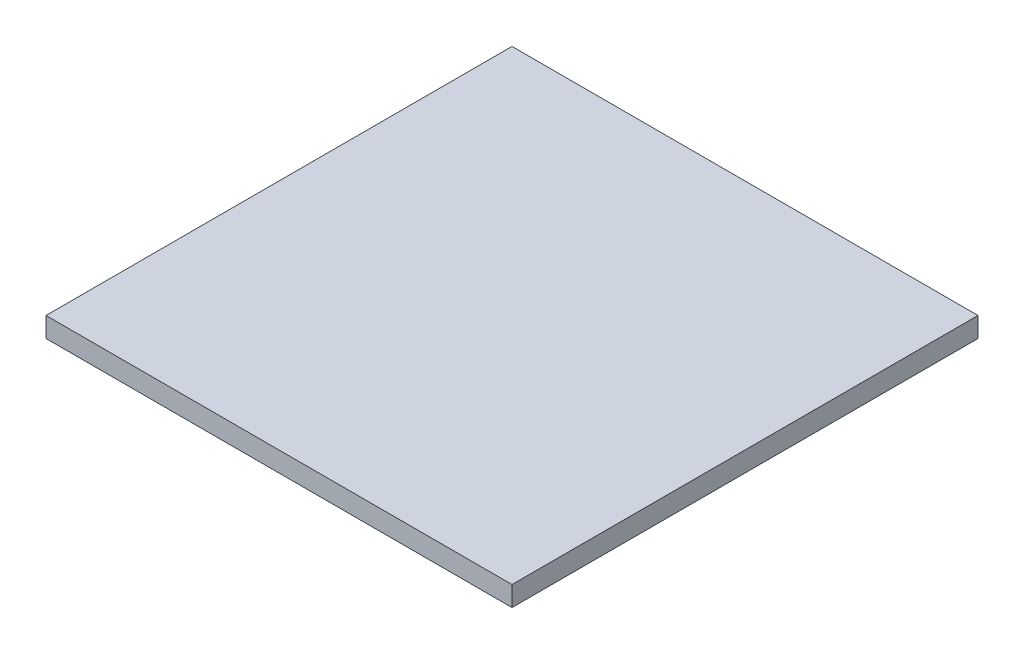
SolidWorks part; units mm, degrees
ref_plane "Front Plane" through (0, 0, 0) normal (0, 0, 1) x (1, 0, 0)
ref_plane "Top Plane" through (0, 0, 0) normal (0, 1, 0) x (1, 0, 0)
ref_plane "Right Plane" through (0, 0, 0) normal (1, 0, 0) x (0, 0, -1)
sketch "Sketch1" plane through (0, 0, 0) normal (0, 1, 0) x (1, 0, 0)
  line L1 (0, 0) -> (711.2, 0)
  line L2 (0, 0) -> (0, -711.2)
  line L3 (0, -711.2) -> (711.2, -711.2)
  line L4 (711.2, 0) -> (711.2, -711.2)
  dimension "D1" = 711.2
  dimension "D2" = 711.2
extrude "Boss-Extrude1" add sketch "Sketch1" along normal blind 30.48
